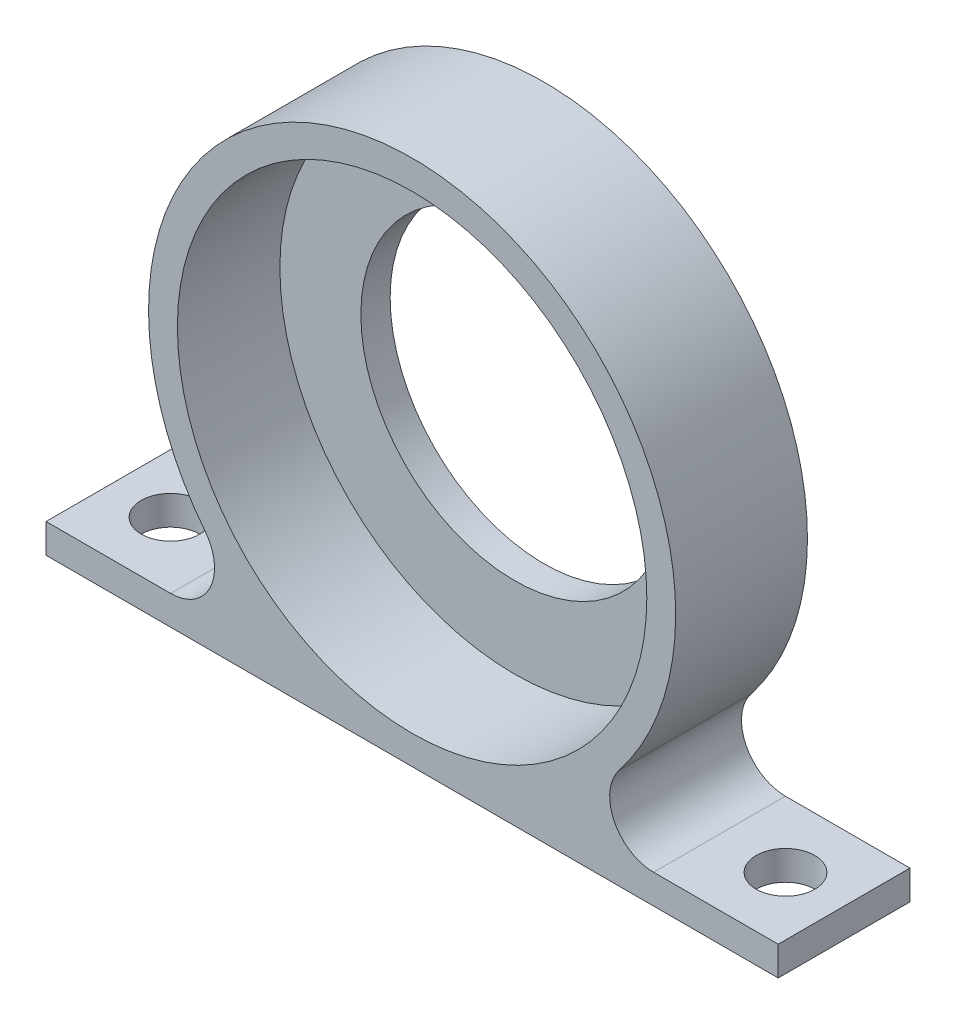
SolidWorks part; units mm, degrees
ref_plane "Alzado" through (0, 0, 0) normal (0, 0, 1) x (1, 0, 0)
ref_plane "Planta" through (0, 0, 0) normal (0, 1, 0) x (1, 0, 0)
ref_plane "Vista lateral" through (0, 0, 0) normal (1, 0, 0) x (0, 0, -1)
sketch "Croquis1" plane through (0, 0, 0) normal (0, 0, 1) x (1, 0, 0)
  line L1 (-25, -16) -> (25, -16)
  line L2 (-25, -16) -> (-25, -18)
  line L3 (-25, -18) -> (25, -18)
  line L4 (25, -16) -> (25, -18)
  line L5 (-25, -16) -> (25, -18) construction
  line L6 (-25, -18) -> (25, -16) construction
  circle A0 centre (0, 0) radius 16.03
  circle A1 centre (0, 0) radius 18
  point P4 (0, -17)
  point P10 (0, -18)
  dimension "D3" = 32.06
  dimension "D1" = 50
  dimension "D2" = 2
  dimension "D4" = 16
extrude "Saliente-Extruir1" add sketch "Croquis1" along normal blind 9 contours L1 A1 A0 | A1 L1 L2 L3 | L1 A1 | A1 L3 L4 L1
sketch "Croquis2" plane through (0, 0, 0) normal (0, 0, -1) x (-1, 0, 0)
  line L5 (-8.2462, -16) -> (-25, -16)
  line L6 (-25, -16) -> (-25, -18)
  line L7 (-25, -18) -> (25, -18)
  line L8 (25, -18) -> (25, -16)
  line L9 (25, -16) -> (8.2462, -16)
  line L10 (-8.2462, -16) -> (-25, -16)
  line L11 (-25, -16) -> (-25, -18)
  line L12 (-25, -18) -> (25, -18)
  line L13 (25, -18) -> (25, -16)
  line L14 (25, -16) -> (8.2462, -16)
  circle A0 centre (0, 0) radius 10.5
  arc A1 (8.2462, -16) -> (-8.2462, -16) centre (0, 0) ccw
  arc A2 (8.2462, -16) -> (-8.2462, -16) centre (0, 0) ccw
  dimension "D2" = 21
  dimension "D1" = 0
extrude "Saliente-Extruir2" add sketch "Croquis2" against normal blind 2
fillet "Redondeo1" radius 3 2 edges at (-8.2462, -16, 4.5) (8.2462, -16, 4.5)
sketch "Croquis3" plane through (0, -16, 0) normal (0, 1, 0) x (1, 0, 0)
  line L0 (-25, -9) -> (-25, 0) construction
  circle A0 centre (-21, -4.5) radius 2
  circle A1 centre (21, -4.5) radius 2
  point P7 (-25, -4.5)
  dimension "D1" = 42
  dimension "D2" = 4
  dimension "D3" = 21
  dimension "D5" = 4
extrude "Cortar-Extruir1" cut sketch "Croquis3" against normal through all
sketch "Croquis4" plane through (0, 0, 9) normal (0, 0, 1) x (1, 0, 0)
  line L0 (25, -16) -> (25, -18) construction
  line L1 (-25, -18) -> (25, -18)
  line L2 (-25, -18) -> (-25, -17.47)
  line L3 (-25, -17.47) -> (25, -17.47)
  line L4 (25, -18) -> (25, -17.47)
  line L5 (-25, -18) -> (25, -17.47) construction
  line L6 (-25, -17.47) -> (25, -18) construction
  point P4 (0, -17.735)
  dimension "D1" = 1.47
equation "\"D3@Croquis1\" = 32 + \"tolerancia\""
equation "\"tolerancia\"= 0.06"
